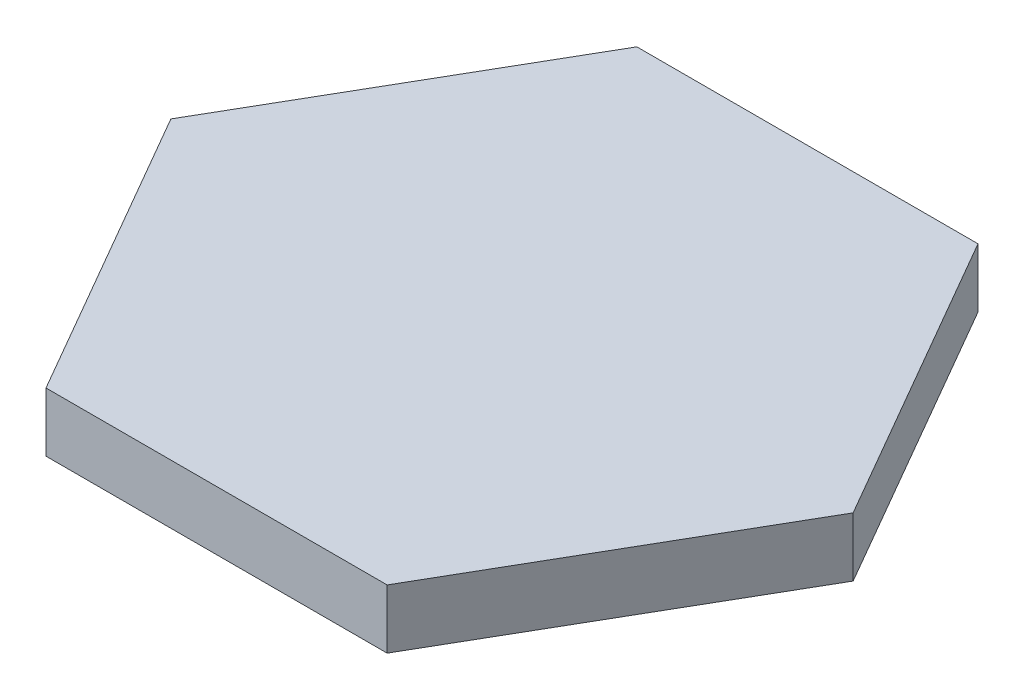
SolidWorks part; units mm, degrees
ref_plane "Front Plane" through (0, 0, 0) normal (0, 0, 1) x (1, 0, 0)
ref_plane "Top Plane" through (0, 0, 0) normal (0, 1, 0) x (1, 0, 0)
ref_plane "Right Plane" through (0, 0, 0) normal (1, 0, 0) x (0, 0, -1)
sketch "Sketch1" plane through (0, 0, 0) normal (0, 1, 0) x (1, 0, 0)
  line L1 (14.4338, -25) -> (28.8675, 0)
  line L2 (28.8675, 0) -> (14.4338, 25)
  line L3 (14.4338, 25) -> (-14.4338, 25)
  line L4 (-14.4338, 25) -> (-28.8675, 0)
  line L5 (-28.8675, 0) -> (-14.4338, -25)
  line L6 (-14.4338, -25) -> (14.4338, -25)
  circle A0 centre (0, 0) radius 25 construction
  dimension "D1" = 50
extrude "Boss-Extrude1" add sketch "Sketch1" along normal blind 5
